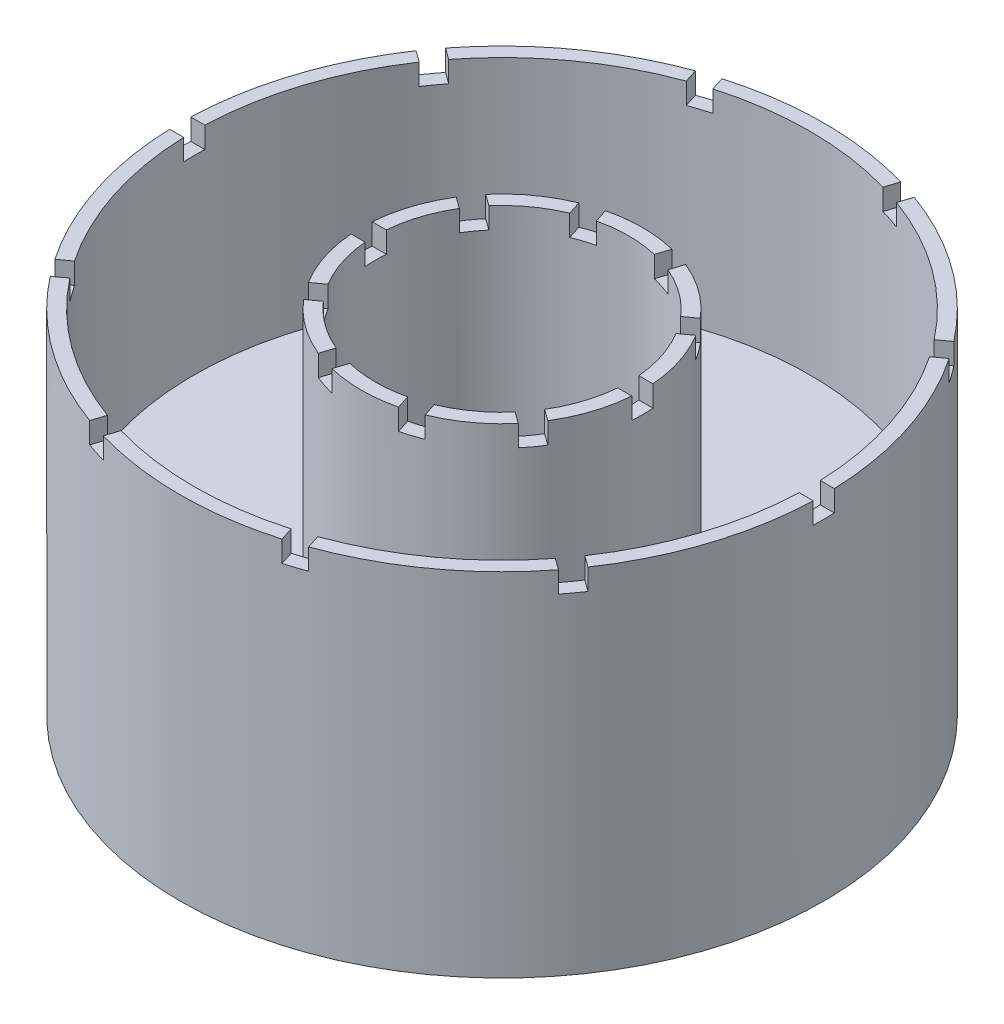
SolidWorks part; units mm, degrees
ref_plane "Front Plane" through (0, 0, 0) normal (0, 0, 1) x (1, 0, 0)
ref_plane "Top Plane" through (0, 0, 0) normal (0, 1, 0) x (1, 0, 0)
ref_plane "Right Plane" through (0, 0, 0) normal (1, 0, 0) x (0, 0, -1)
sketch "Sketch1" plane through (0, 0, 0) normal (0, 0, 1) x (1, 0, 0)
  line L0 (-7.2, -4) -> (-7.2, 12)
  line L1 (-7.2, 12) -> (-8, 12)
  line L2 (-8, 12) -> (-8, 0)
  line L3 (-8, 0) -> (-17.5, 0)
  line L4 (-17.5, 0) -> (-17.5, 12)
  line L5 (-17.5, 12) -> (-18.3, 12)
  line L6 (-18.3, 12) -> (-18.3, -8)
  line L7 (-18.3, -8) -> (-4.3, -8)
  line L8 (-4.3, -8) -> (-4.3, -4)
  line L9 (0, 0) -> (0, -15.3118) construction
  line L11 (-7.2, -4) -> (-4.3, -4)
  dimension "D1" = 0.8
  dimension "D2" = 8
  dimension "D3" = 8
  dimension "D4" = 12
  dimension "D5" = 17.5
  dimension "D6" = 4
  dimension "D7" = 4.3
revolve "Revolve1" add sketch "Sketch1" angle 360 about L9
sketch "Sketch4" plane through (0, 0, 0) normal (1, 0, 0) x (0, 0, -1)
  line L0 (18.3, 12) -> (-18.3, 12) construction
  line L1 (0.6, 10.8) -> (-0.6, 10.8)
  line L2 (0.6, 10.8) -> (0.6, 12)
  line L3 (0.6, 12) -> (-0.6, 12)
  line L4 (-0.6, 10.8) -> (-0.6, 12)
  line L5 (0.6, 10.8) -> (-0.6, 12) construction
  line L6 (0.6, 12) -> (-0.6, 10.8) construction
  point P0 (0, 11.4)
  point P7 (0.6239, 9.2017)
  point P8 (0, 0)
  point P10 (0.6, 10.1379)
  dimension "D1" = 1.2
  dimension "D2" = 1.2
extrude "Cut-Extrude2" cut sketch "Sketch4" against normal through all
pattern_circular "CirPattern1" count 10 over 360 about axis through (0, 0, 0) along (0, 1, 0) of "Cut-Extrude2"
